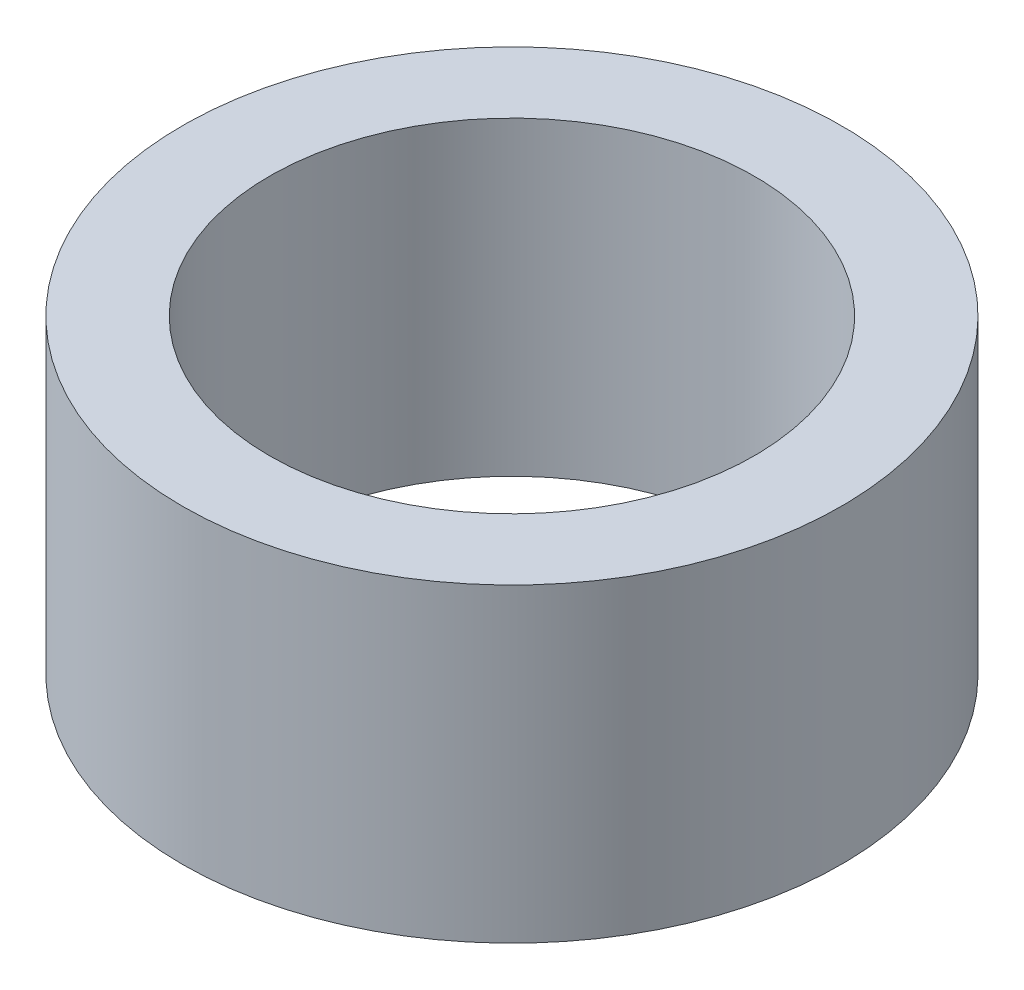
SolidWorks part; units mm, degrees
ref_plane "Front Plane" through (0, 0, 0) normal (0, 0, 1) x (1, 0, 0)
ref_plane "Top Plane" through (0, 0, 0) normal (0, 1, 0) x (1, 0, 0)
ref_plane "Right Plane" through (0, 0, 0) normal (1, 0, 0) x (0, 0, -1)
sketch "Sketch1" plane through (0, 0, 0) normal (0, 1, 0) x (1, 0, 0)
  circle A0 centre (0, 0) radius 3.125
  circle A1 centre (0, 0) radius 4.25
  dimension "D1" = 6.25
  dimension "D2" = 8.5
extrude "Boss-Extrude1" add sketch "Sketch1" along normal blind 4
